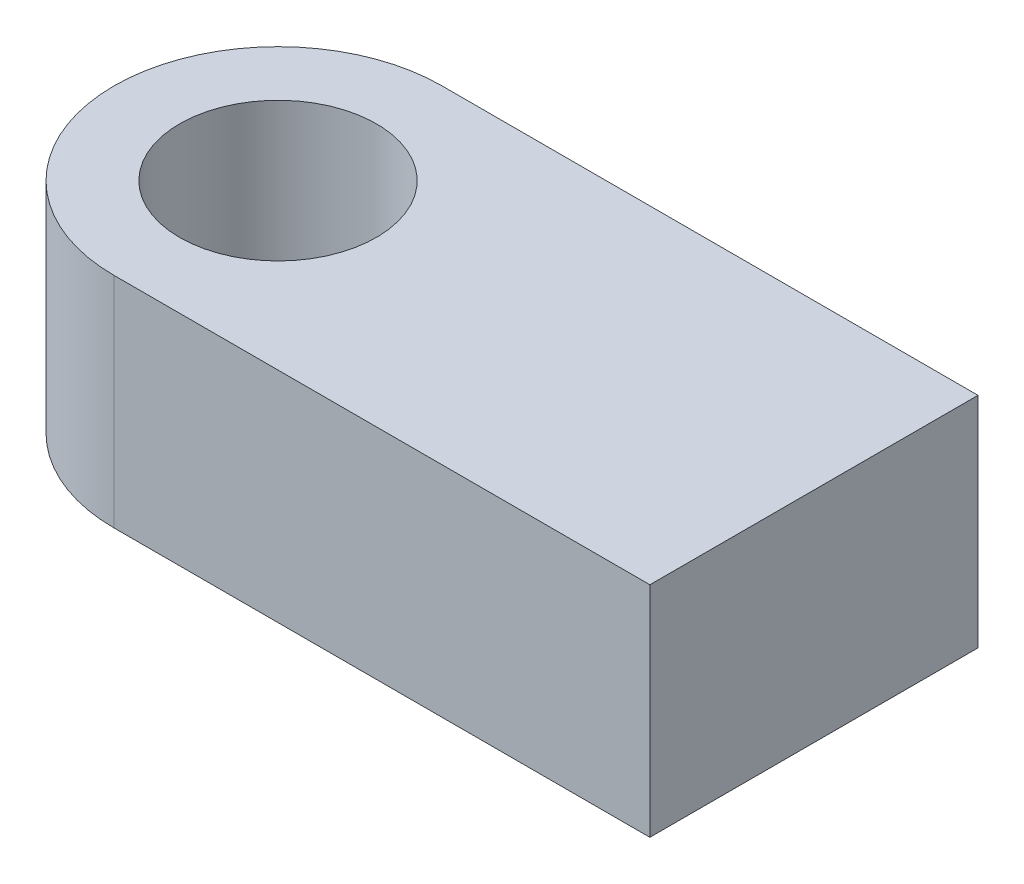
SolidWorks part; units mm, degrees
ref_plane "Спереди" through (0, 0, 0) normal (0, 0, 1) x (1, 0, 0)
ref_plane "Сверху" through (0, 0, 0) normal (0, 1, 0) x (1, 0, 0)
ref_plane "Справа" through (0, 0, 0) normal (1, 0, 0) x (0, 0, -1)
sketch "Эскиз1" plane through (0, 0, 0) normal (0, 1, 0) x (1, 0, 0)
  line L0 (0, 0) -> (23.3605, 0) construction
  line L1 (4.5, 0) -> (4.5, -13.7008) construction
  line L2 (24.5, -7.5) -> (0, -7.5)
  line L3 (24.5, -7.5) -> (24.5, 7.5)
  line L4 (24.5, 7.5) -> (0, 7.5)
  circle A0 centre (0, 0) radius 4.5
  arc A1 (0, 7.5) -> (0, -7.5) centre (0, 0) ccw
  point P13 (0, 7.5)
  point P14 (0, -7.5)
  point P15 (0, 0)
  dimension "D1" = 9
  dimension "D2" = 15
  dimension "D3" = 15
  dimension "D4" = 20
extrude "Бобышка-Вытянуть1" add sketch "Эскиз1" along normal blind 10
